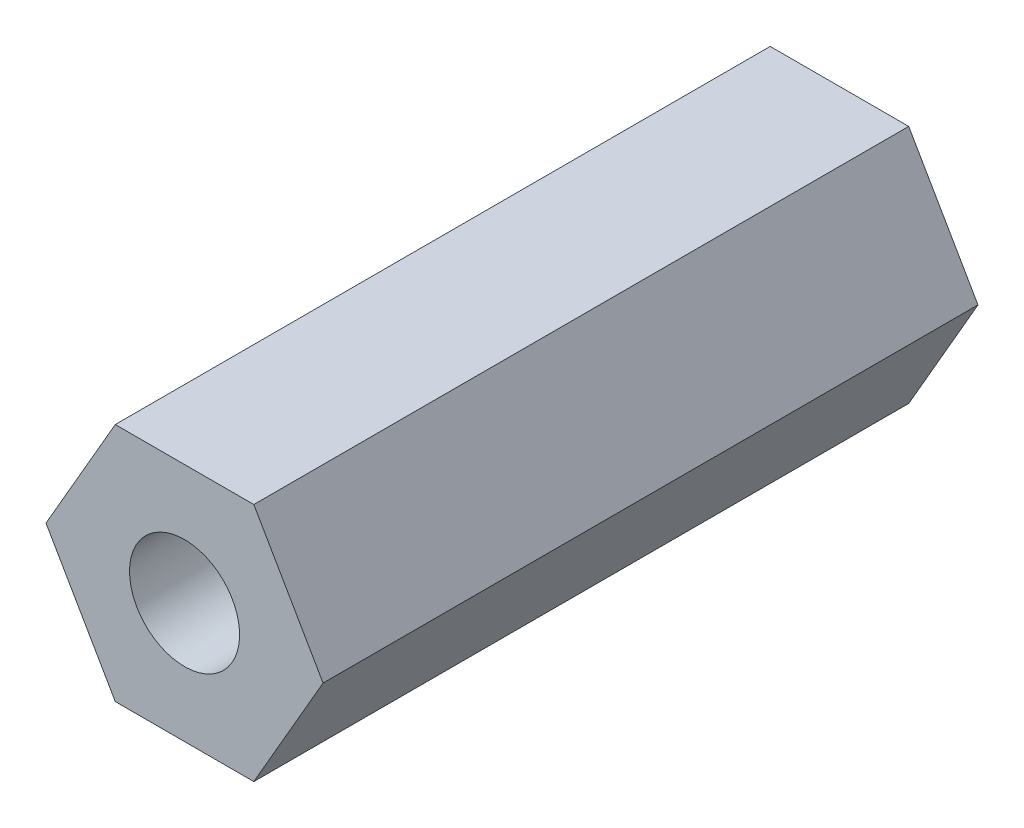
SolidWorks part; units mm, degrees
ref_plane "Front Plane" through (0, 0, 0) normal (0, 0, 1) x (1, 0, 0)
ref_plane "Top Plane" through (0, 0, 0) normal (0, 1, 0) x (1, 0, 0)
ref_plane "Right Plane" through (0, 0, 0) normal (1, 0, 0) x (0, 0, -1)
sketch "Sketch1" plane through (0, 0, 0) normal (0, 0, 1) x (1, 0, 0)
  line L1 (-3.1969, 0) -> (-1.5985, -2.7686)
  line L2 (-1.5985, -2.7686) -> (1.5985, -2.7686)
  line L3 (1.5985, -2.7686) -> (3.1969, 0)
  line L4 (3.1969, 0) -> (1.5985, 2.7686)
  line L5 (1.5985, 2.7686) -> (-1.5985, 2.7686)
  line L6 (-1.5985, 2.7686) -> (-3.1969, 0)
  circle A0 centre (0, 0) radius 2.7686 construction
  dimension "D1" = 5.5372
extrude "Boss-Extrude1" add sketch "Sketch1" along normal blind 15.113
sketch "Sketch2" plane through (0, 0, 0) normal (0, 0, -1) x (-1, 0, 0)
  circle A0 centre (0, 0) radius 1.27
extrude "Cut-Extrude1" cut sketch "Sketch2" against normal through all
